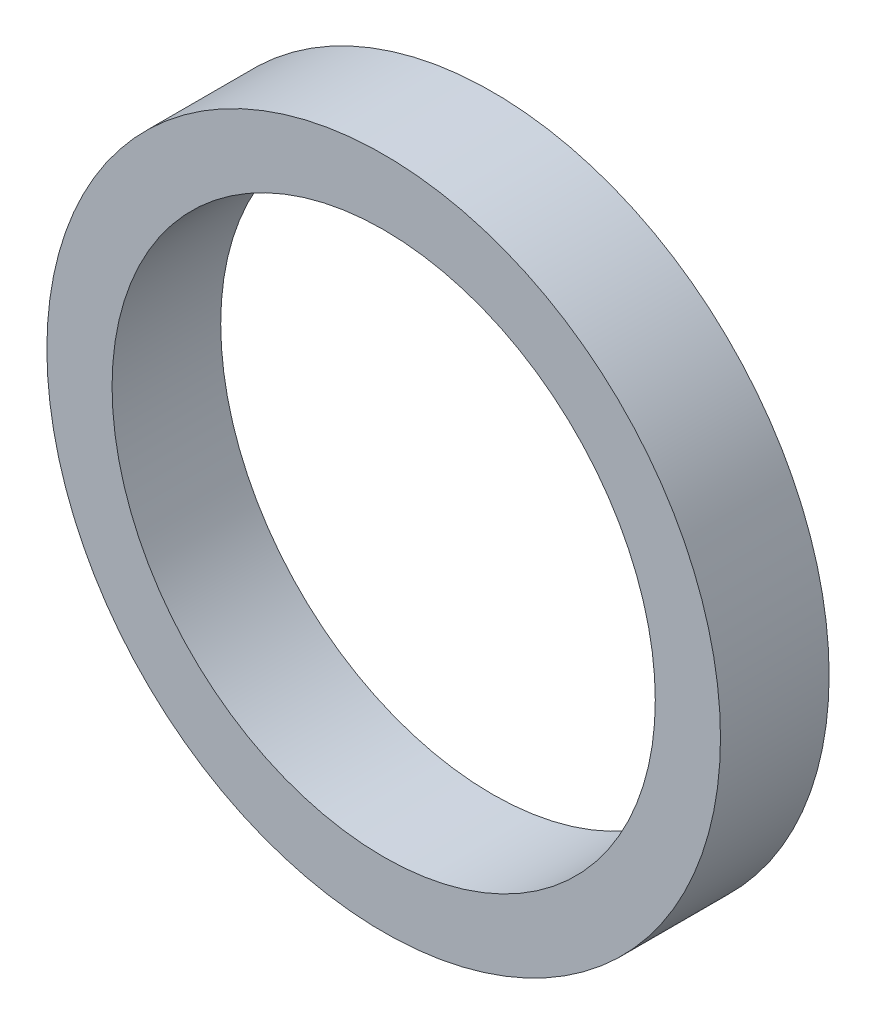
SolidWorks part; units mm, degrees
material "1060 合金"
ref_plane "前视基准面" through (0, 0, 0) normal (0, 0, 1) x (1, 0, 0)
ref_plane "上视基准面" through (0, 0, 0) normal (0, 1, 0) x (1, 0, 0)
ref_plane "右视基准面" through (0, 0, 0) normal (1, 0, 0) x (0, 0, -1)
sketch "草图1" plane through (0, 0, 0) normal (0, 0, 1) x (1, 0, 0)
  circle A1 centre (0, 0) radius 12.5
  circle A2 centre (0, 0) radius 15.5
  dimension "D1" = 3
extrude "凸台-拉伸1" add sketch "草图1" along normal blind 5
